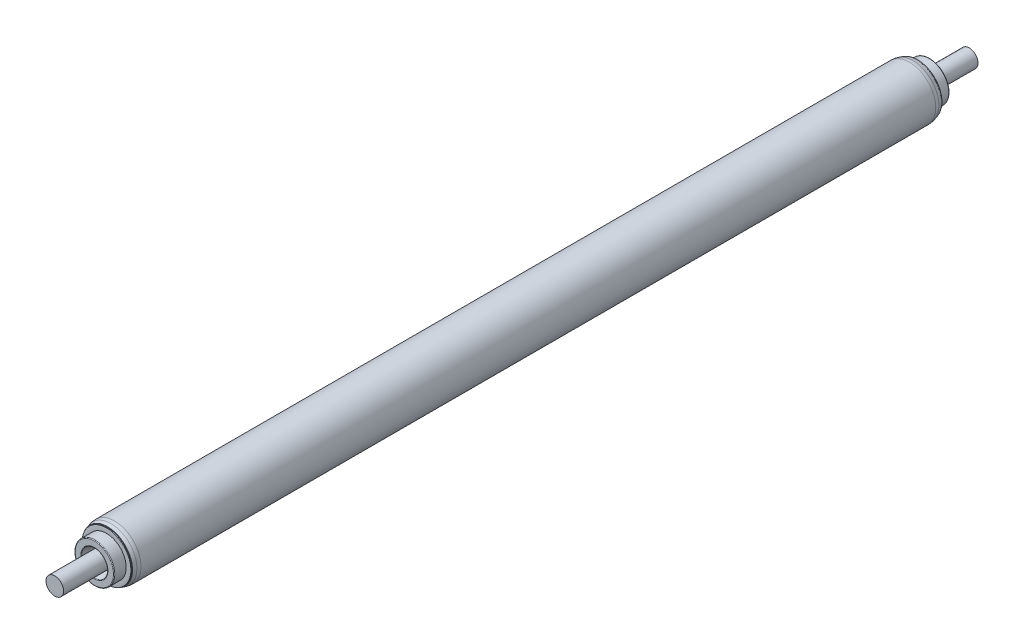
SolidWorks part; units mm, degrees
ref_plane "Front Plane" through (0, 0, 0) normal (0, 0, 1) x (1, 0, 0)
ref_plane "Top Plane" through (0, 0, 0) normal (0, 1, 0) x (1, 0, 0)
ref_plane "Right Plane" through (0, 0, 0) normal (1, 0, 0) x (0, 0, -1)
sketch "Sketch1" plane through (0, 0, 0) normal (1, 0, 0) x (0, 0, -1)
  line L0 (-152.4, 0) -> (152.4, 0) construction
  line L1 (-152.4, 0) -> (-165.1, 0) construction
  line L2 (152.4, 0) -> (165.1, 0) construction
  line L3 (-146.05, 0) -> (146.05, 0) construction
  line L4 (-165.1, -3.175) -> (-165.1, 3.175) construction
  line L5 (-146.05, -9.525) -> (-146.05, 9.525) construction
  line L6 (165.1, 3.175) -> (165.1, -3.175) construction
  point P8 (88.9, 0)
  point P10 (-88.9, 0)
  point P18 (-152.4, 3.175)
  point P19 (-146.05, 8.509)
  point P21 (152.4, 3.175)
  point P22 (146.05, 9.525)
  dimension "Between Frame Width" = 304.8
  dimension "Overall Width" = 330.2
  dimension "Roller Width" = 292.1
  dimension "D1" = 76.2
  dimension "D2" = 76.2
  dimension "Axle OD" = 6.35
  dimension "Roller OD" = 19.05
  dimension "Roller Thickness" = 1.016
sketch "Sketch2" plane through (0, 0, 0) normal (0, 0, 1) x (1, 0, 0)
  circle A0 centre (0, 0) radius 3.175
  circle A1 centre (0, 0) radius 9.525 construction
extrude "Boss-Extrude1" add sketch "Sketch2" along normal up to vertex (165.1 mm away) and the other way up to vertex (165.1 mm away) up to point (0, 0, 165.1) other way up to point (0, 0, -165.1)
sketch "Sketch3" plane through (0, 0, 0) normal (-1, 0, 0) x (0, 0, 1)
  line L0 (138.1125, 7.1425) -> (150.5585, 7.1425)
  line L1 (150.8125, 6.8885) -> (150.8125, 4.9159)
  line L2 (138.1125, 3.175) -> (138.1125, 7.1425)
  line L3 (138.1125, 3.175) -> (150.8125, 3.175) construction
  line L4 (165.1, 3.175) -> (-165.1, 3.175) construction
  line L5 (150.8125, 3.175) -> (150.8125, 4.7625) construction
  line L6 (152.4, 7.1425) -> (150.8125, 7.1425) construction
  line L7 (138.1125, 3.175) -> (144.4625, 3.175)
  line L11 (165.1, 0) -> (0, 0) construction
  arc A0 (144.4625, 3.175) -> (150.6754, 4.6904) centre (144.4625, 16.6688) ccw
  arc A1 (150.8125, 4.9159) -> (150.6754, 4.6904) centre (150.5585, 4.9159) cw
  arc A2 (150.5585, 7.1425) -> (150.8125, 6.8885) centre (150.5585, 6.8885) cw
  dimension "D1" = 1.5875
  dimension "D3" = 0.254
  dimension "D2" = 2.38
  dimension "D4" = 12.7
revolve "Revolve1" add sketch "Sketch3" angle 360 mid plane about L11
sketch "Sketch6" plane through (0, 0, 0) normal (1, 0, 0) x (0, 0, -1)
  line L6 (-146.05, 9.017) -> (-144.8001, 9.3519)
  line L32 (-146.05, -9.525) -> (-146.05, 9.525) construction
  line L33 (-143.4853, 9.525) -> (143.4853, 9.525)
  line L35 (-143.7452, 8.509) -> (143.7452, 8.509)
  line L36 (0, 0) -> (0, 9.525) construction
  line L37 (-152.4, 0) -> (152.4, 0) construction
  line L38 (-146.05, 8.509) -> (-146.05, 9.525) construction
  line L40 (-146.05, 9.017) -> (-146.05, 8.9154)
  line L41 (-146.05, 8.9154) -> (-143.7452, 8.509)
  line L42 (146.05, 9.017) -> (144.8001, 9.3519)
  line L43 (146.05, 9.017) -> (146.05, 8.9154)
  line L44 (146.05, 8.9154) -> (143.7452, 8.509)
  arc A7 (-144.8001, 9.3519) -> (-143.4853, 9.525) centre (-143.4853, 4.445) cw
  arc A8 (144.8001, 9.3519) -> (143.4853, 9.525) centre (143.4853, 4.445) ccw
  point P24 (0, 8.509)
  dimension "D1" = 15
  dimension "D2" = 5.08
  dimension "D3" = 10
  dimension "D4" = 0.1016
revolve "Revolve4" add sketch "Sketch6" angle 360 about L0
sketch "Sketch4" plane through (0, 0, 0) normal (1, 0, 0) x (0, 0, -1)
  line L5 (-140.0175, 7.7227) -> (-140.0175, 7.1425)
  line L6 (-141.6939, 7.6315) -> (-141.6939, 7.1425)
  line L7 (-138.1125, 7.1425) -> (-150.5585, 7.1425) construction
  line L8 (-141.6939, 7.1425) -> (-140.0175, 7.1425)
  line L9 (-146.177, 8.8088) -> (-146.177, 8.885)
  line L10 (-146.177, 8.885) -> (-146.431, 8.817)
  line L17 (-140.0175, 7.7227) -> (-146.177, 8.8088)
  line L18 (-146.05, 9.017) -> (-146.05, 8.9154) construction
  line L20 (-146.431, 6.785) -> (-146.431, 8.817) construction
  line L24 (-143.7983, 8.0025) -> (-141.6939, 7.6315)
  line L25 (-146.05, 8.9154) -> (-143.7452, 8.509) construction
  line L26 (-138.1125, 3.175) -> (-138.1125, 7.1425) construction
  line L28 (-146.05, 9.017) -> (-144.8001, 9.3519) construction
  arc A5 (-146.431, 6.785) -> (-143.7983, 8.0025) centre (-144.2394, 5.5011) cw
  arc A6 (-146.431, 8.817) -> (-146.431, 6.785) centre (-136.2964, 7.801) ccw
  dimension "D1" = 0.127
  dimension "D3" = 2.032
  dimension "D4" = 0.127
  dimension "D5" = 0.254
  dimension "D2" = 2.54
  dimension "D10" = 0.0508
  dimension "D6" = 1.6764
  dimension "D7" = 1.905
  dimension "D8" = 0.381
  dimension "D9" = 0.0762
revolve "Revolve2" add sketch "Sketch4" angle 360 about L0
sketch "Sketch5" plane through (0, 0, 0) normal (1, 0, 0) x (0, 0, -1)
  line L0 (-141.6939, 7.532) -> (-143.2661, 6.6243)
  line L1 (-141.6939, 7.6315) -> (-141.6939, 7.1425) construction
  line L2 (-144.4975, 4.8656) -> (-144.0624, 7.333)
  line L4 (-144.0624, 7.333) -> (-141.6939, 7.333)
  line L5 (-141.6939, 7.333) -> (-141.6939, 7.532)
  line L6 (-144.0624, 7.333) -> (-146.431, 7.333) construction
  line L7 (-141.6939, 7.6315) -> (-141.6939, 7.532) construction
  line L8 (-141.6939, 7.532) -> (-141.6939, 7.4325) construction
  line L9 (-141.6939, 7.4325) -> (-141.6939, 7.333) construction
  line L10 (-152.4, 7.1425) -> (-150.8125, 7.1425) construction
  arc A0 (-143.2661, 6.6243) -> (-144.4975, 4.8656) centre (-141.9961, 4.4246) ccw
  dimension "D1" = 10
  dimension "D3" = 2.54
  dimension "D2" = 60
  dimension "D4" = 0.1905
revolve "Revolve3" add sketch "Sketch5" angle 360 about L0
mirror "Mirror1" about plane through (0, 0, 0) normal (0, 0, 1) of bodies 102 105 106
equation "\"D2@Sketch1\"=\"D1@Sketch1\""
